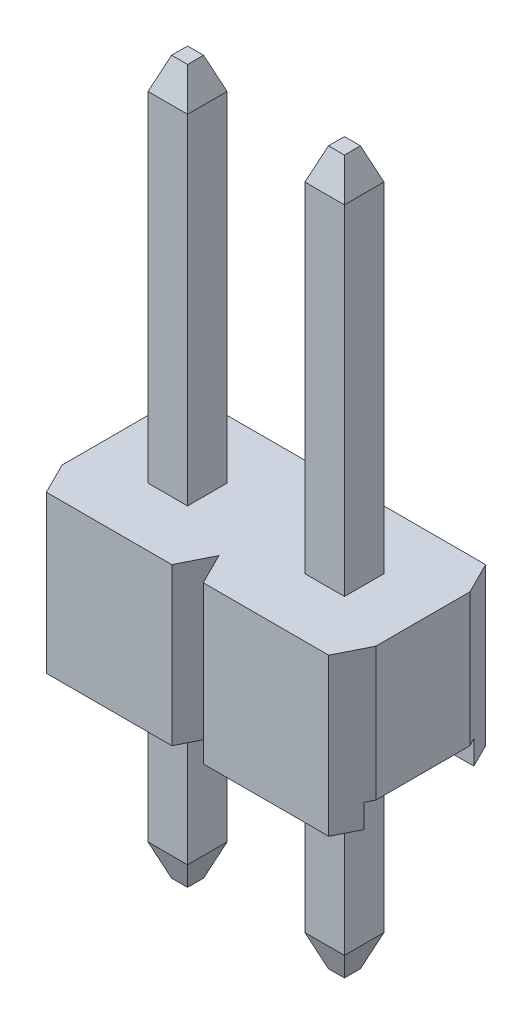
SolidWorks part; units mm, degrees
ref_plane "Front Plane" through (0, 0, 0) normal (0, 0, 1) x (1, 0, 0)
ref_plane "Top Plane" through (0, 0, 0) normal (0, 1, 0) x (1, 0, 0)
ref_plane "Right Plane" through (0, 0, 0) normal (1, 0, 0) x (0, 0, -1)
sketch "Sketch1" plane through (0, 0, 0) normal (0, 1, 0) x (1, 0, 0)
  line L1 (0, 0) -> (2.54, 0)
  line L2 (0, 0) -> (0, 2.54)
  line L3 (0, 2.54) -> (2.54, 2.54)
  line L4 (2.54, 0) -> (2.54, 2.54)
  dimension "D1" = 2.54
  dimension "D2" = 2.54
extrude "Main Body" add sketch "Sketch1" along normal blind 2.54
sketch "Sketch3" plane through (0, 0, 0) normal (-1, 0, 0) x (0, 0, 1)
  line L0 (-2.54, 0) -> (0, 0) construction
  line L1 (-2.159, 0) -> (-0.381, 0)
  line L2 (-2.159, 0) -> (-2.159, 0.381)
  line L3 (-2.159, 0.381) -> (-0.381, 0.381)
  line L4 (-0.381, 0) -> (-0.381, 0.381)
  line L5 (-2.54, 0) -> (-2.159, 0) construction
  line L6 (-0.381, 0) -> (0, 0) construction
  dimension "D1" = 0.381
extrude "Cut-Extrude1" cut sketch "Sketch3" against normal through all
sketch "Sketch4" plane through (0, 2.54, 0) normal (0, 1, 0) x (1, 0, 0)
  line L0 (0, 2.54) -> (0, 2.032)
  line L1 (0, 2.54) -> (0, 0) construction
  line L2 (0, 2.032) -> (0.254, 2.54)
  line L3 (2.54, 2.54) -> (0, 2.54) construction
  line L4 (0.254, 2.54) -> (0, 2.54)
  line L5 (2.54, 2.54) -> (2.286, 2.54)
  line L6 (2.286, 2.54) -> (2.54, 2.032)
  line L7 (2.54, 0) -> (2.54, 2.54) construction
  line L8 (2.54, 2.032) -> (2.54, 2.54)
  line L9 (2.54, 0) -> (2.286, 0)
  line L10 (0, 0) -> (2.54, 0) construction
  line L11 (2.286, 0) -> (2.54, 0.508)
  line L12 (2.54, 0.508) -> (2.54, 0)
  line L14 (0, 0) -> (0, 0.508)
  line L15 (0, 0.508) -> (0.254, 0)
  line L16 (0.254, 0) -> (0, 0)
  line M1 (0, 2.54) -> (0, 0)
  line M2 (0, 0) -> (2.54, 0)
  line M3 (2.54, 0) -> (2.54, 2.54)
  line M4 (2.54, 2.54) -> (0, 2.54)
  dimension "D1" = 0.254
  dimension "D2" = 0.508
extrude "Cut-Extrude2" cut sketch "Sketch4" against normal through all contours L2 M1 M4 | L6 M4 M3 | L15 M1 M2 | L9 L11 L12
pattern_linear "Body Pattern" count 2 spacing 2.54 along (-1, 0, 0) of "Main Body", "Cut-Extrude1", "Cut-Extrude2"
sketch "Sketch2" plane through (0, 2.54, 0) normal (0, 1, 0) x (1, 0, 0)
  line L0 (1.27, 2.54) -> (1.27, 1.59) construction
  line L1 (0.95, 0.95) -> (1.59, 0.95)
  line L2 (0.95, 0.95) -> (0.95, 1.59)
  line L3 (0.95, 1.59) -> (1.59, 1.59)
  line L4 (1.59, 0.95) -> (1.59, 1.59)
  line L6 (2.286, 2.54) -> (0.254, 2.54) construction
  line L8 (1.27, 0.95) -> (1.27, 0) construction
  line L9 (0.254, 0) -> (2.286, 0) construction
  dimension "D1" = 0.64
extrude "Pin" add sketch "Sketch2" along normal blind 6 and the other way offset from surface (5.54 mm away) 3 other way up to face at (1.27, 0, -0.1905)
chamfer "Chamfer1" distance 0.508 distance2 0.1905 4 edges at (0.95, 8.54, -1.27) (1.27, 8.54, -1.59) (1.59, 8.54, -1.27) (1.27, 8.54, -0.95)
chamfer "Chamfer2" distance 0.1905 distance2 0.508 4 edges at (1.27, -3, -1.59) (1.59, -3, -1.27) (1.27, -3, -0.95) (0.95, -3, -1.27)
pattern_linear "Pin Pattern" count 2 spacing 2.54 along (-1, 0, 0) of "Pin", "Chamfer1", "Chamfer2"
